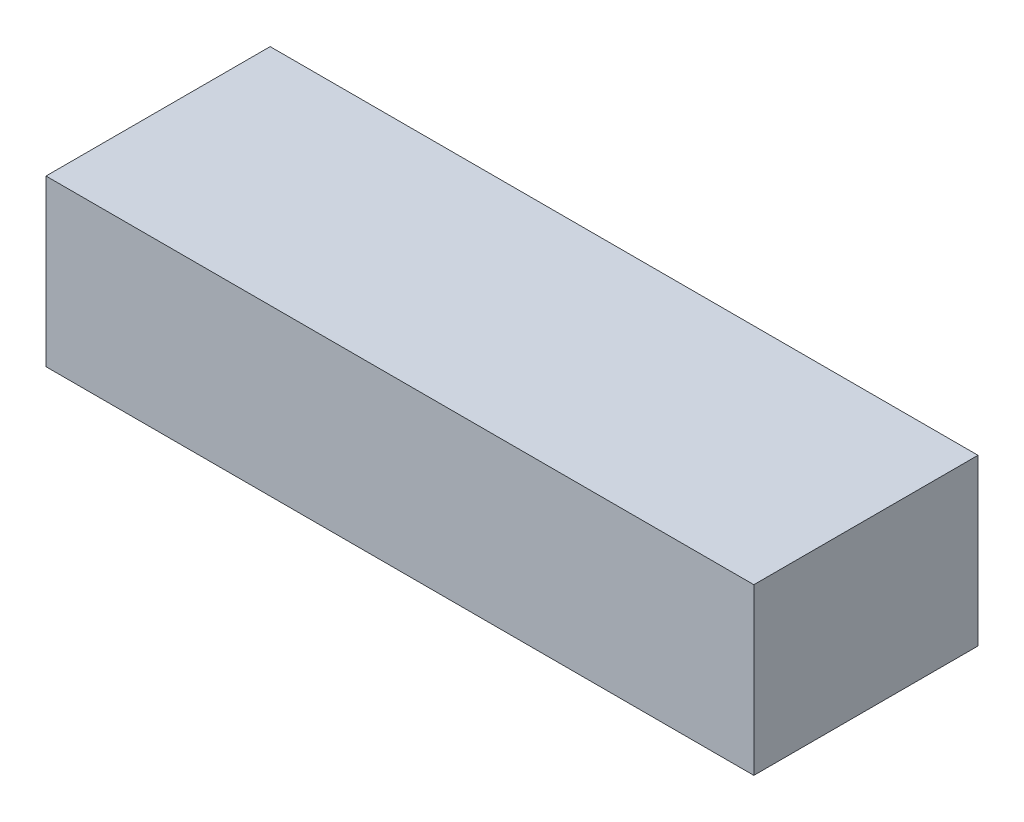
SolidWorks part; units mm, degrees
ref_plane "Front Plane" through (0, 0, 0) normal (0, 0, 1) x (1, 0, 0)
ref_plane "Top Plane" through (0, 0, 0) normal (0, 1, 0) x (1, 0, 0)
ref_plane "Right Plane" through (0, 0, 0) normal (1, 0, 0) x (0, 0, -1)
sketch "Sketch1" plane through (0, 0, 0) normal (0, 1, 0) x (1, 0, 0)
  line L1 (0, 0) -> (60, 0)
  line L2 (0, 0) -> (0, 19)
  line L3 (0, 19) -> (60, 19)
  line L4 (60, 0) -> (60, 19)
  dimension "D1" = 19
  dimension "D2" = 60
extrude "Boss-Extrude1" add sketch "Sketch1" along normal blind 14
